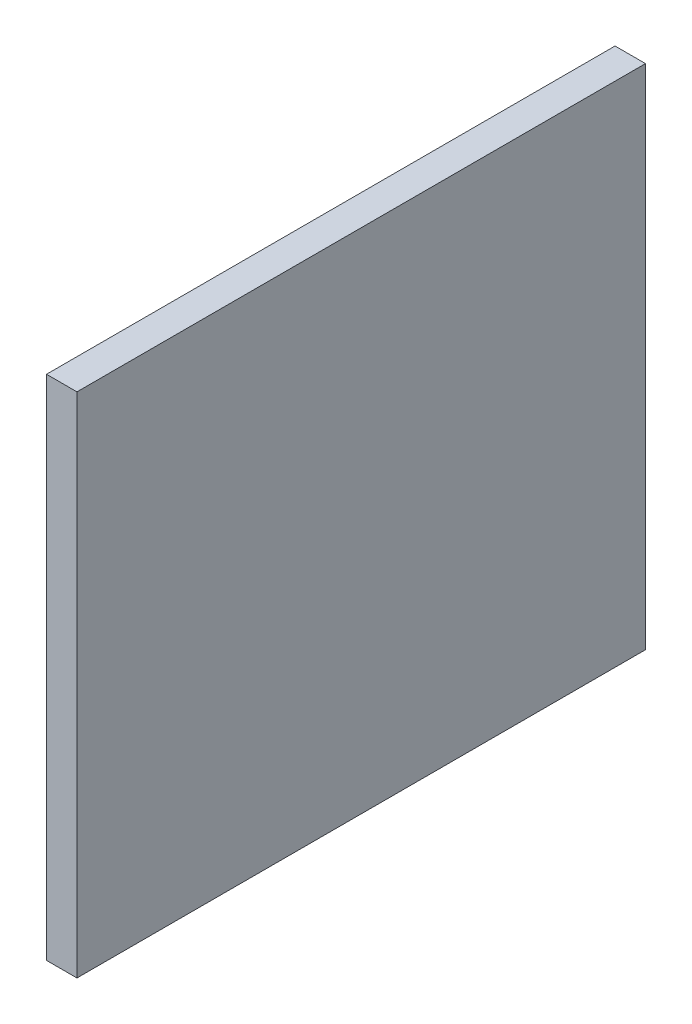
SolidWorks part; units mm, degrees
ref_plane "Front Plane" through (0, 0, 0) normal (0, 0, 1) x (1, 0, 0)
ref_plane "Top Plane" through (0, 0, 0) normal (0, 1, 0) x (1, 0, 0)
ref_plane "Right Plane" through (0, 0, 0) normal (1, 0, 0) x (0, 0, -1)
sketch "Sketch1" plane through (0, 0, 0) normal (1, 0, 0) x (0, 0, -1)
  line L1 (-28, 25) -> (28, 25)
  line L2 (-28, 25) -> (-28, -25)
  line L3 (-28, -25) -> (28, -25)
  line L4 (28, 25) -> (28, -25)
  line L5 (0, -25) -> (0, 25) construction
  line L6 (-28, 0) -> (28, 0) construction
  point P0 (0, 0)
  dimension "D1" = 56
  dimension "D2" = 50
extrude "Boss-Extrude1" add sketch "Sketch1" along normal blind 3
sketch "Sketch2" plane through (3, 0, 0) normal (1, 0, 0) x (0, 0, -1)
  circle A0 centre (-12.7681, 0) radius 8
  circle A1 centre (13.7319, 0) radius 8
  point P4 (0, 0)
  point P5 (0, 0)
  point P6 (0, 0)
  point P8 (0, 0)
  dimension "D2" = 16
  dimension "D1" = 26.5
  dimension "D3" = 12.7681
